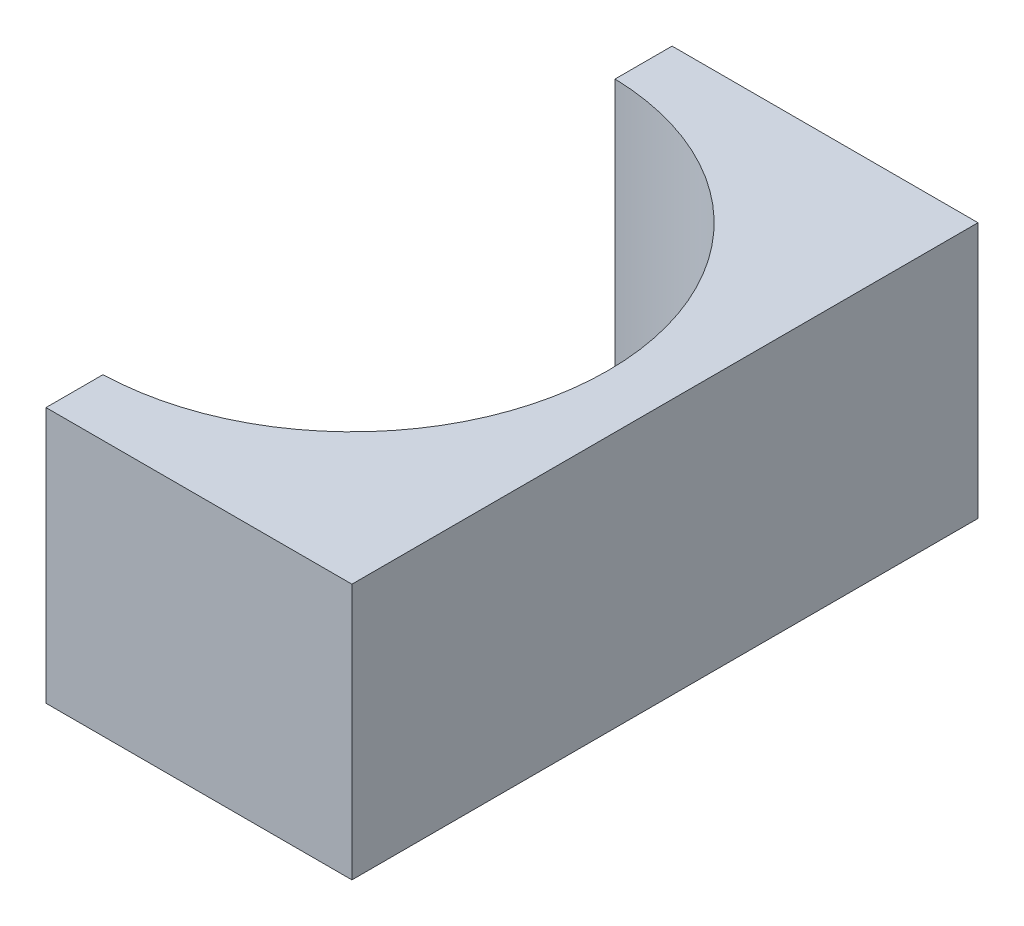
SolidWorks part; units mm, degrees
material "6061 Alloy"
ref_plane "Front Plane" through (0, 0, 0) normal (0, 0, 1) x (1, 0, 0)
ref_plane "Top Plane" through (0, 0, 0) normal (0, 1, 0) x (1, 0, 0)
ref_plane "Right Plane" through (0, 0, 0) normal (1, 0, 0) x (0, 0, -1)
sketch "Sketch1" plane through (0, 0, 0) normal (0, 1, 0) x (1, 0, 0)
  line L0 (0, 55.88) -> (0, 50.7912)
  line L1 (0, 0) -> (27.305, 0)
  line L2 (0, 0) -> (0, 5.0888)
  line L3 (0, 55.88) -> (27.305, 55.88)
  line L4 (27.305, 0) -> (27.305, 55.88)
  arc A0 (0, 50.7912) -> (0, 5.0888) centre (-0.635, 27.94) cw
  dimension "D4" = 22.86
  dimension "D1" = 55.88
  dimension "D2" = 27.305
  dimension "D3" = 0.635
extrude "Boss-Extrude1" add sketch "Sketch1" along normal blind 22.86
